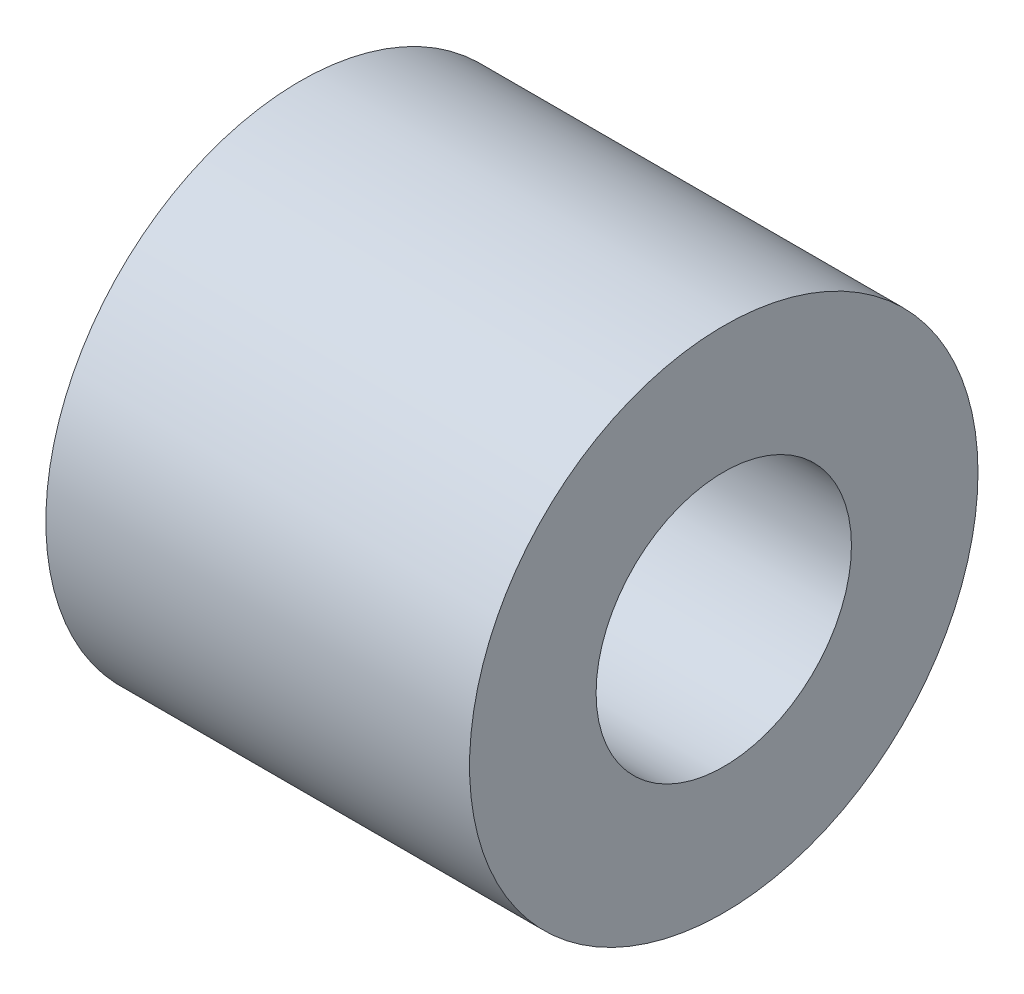
SolidWorks part; units mm, degrees
material "Acero al carbono fundido"
ref_plane "Alzado" through (0, 0, 0) normal (0, 0, 1) x (1, 0, 0)
ref_plane "Planta" through (0, 0, 0) normal (0, 1, 0) x (1, 0, 0)
ref_plane "Vista lateral" through (0, 0, 0) normal (1, 0, 0) x (0, 0, -1)
sketch "Croquis2" plane through (0, 0, 0) normal (1, 0, 0) x (0, 0, -1)
  circle A0 centre (0, 0) radius 6
extrude "Saliente-Extruir1" add sketch "Croquis2" along normal blind 10
sketch "Croquis3" plane through (0, 0, 0) normal (-1, 0, 0) x (0, 0, 1)
  circle A0 centre (0, 0) radius 3.0132
extrude "Cortar-Extruir1" cut sketch "Croquis3" against normal blind 10
